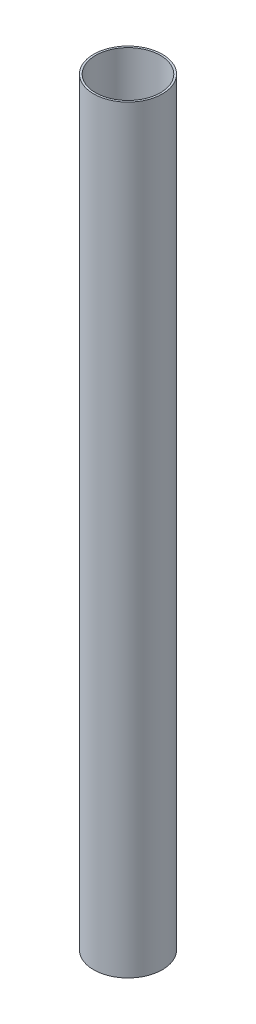
SolidWorks part; units mm, degrees
ref_plane "Front Plane" through (0, 0, 0) normal (0, 0, 1) x (1, 0, 0)
ref_plane "Top Plane" through (0, 0, 0) normal (0, 1, 0) x (1, 0, 0)
ref_plane "Right Plane" through (0, 0, 0) normal (1, 0, 0) x (0, 0, -1)
sketch "Sketch1" plane through (0, 0, 0) normal (0, 1, 0) x (1, 0, 0)
  circle A0 centre (0, 0) radius 25.4635
  circle A1 centre (0, 0) radius 26.9875
  dimension "D1" = 53.975
  dimension "D2" = 50.927
extrude "Boss-Extrude1" add sketch "Sketch1" along normal blind 595.7316
